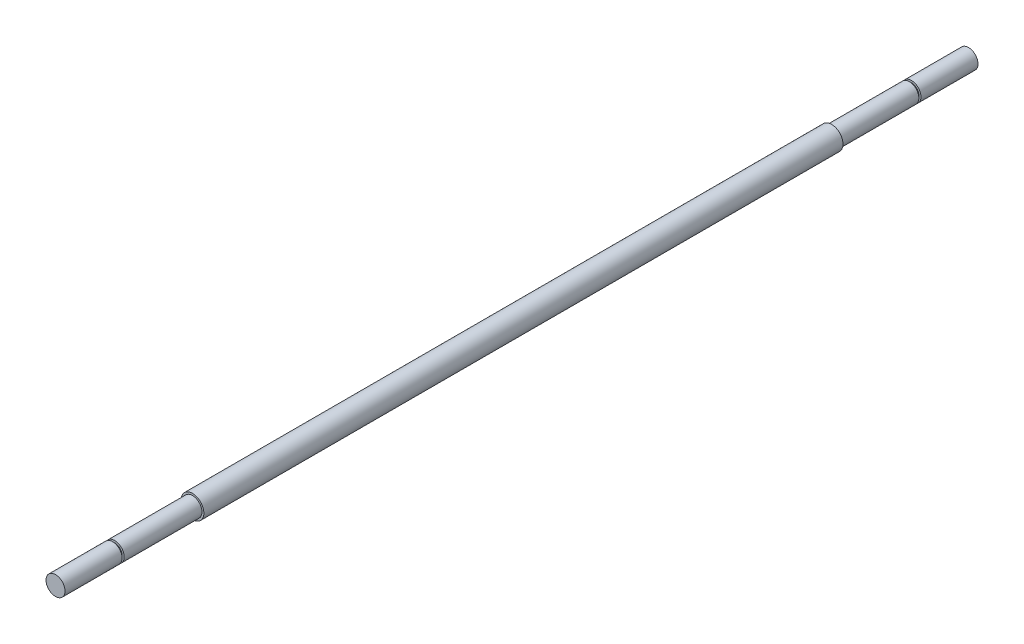
SolidWorks part; units mm, degrees
ref_plane "Front Plane" through (0, 0, 0) normal (0, 0, 1) x (1, 0, 0)
ref_plane "Top Plane" through (0, 0, 0) normal (0, 1, 0) x (1, 0, 0)
ref_plane "Right Plane" through (0, 0, 0) normal (1, 0, 0) x (0, 0, -1)
sketch "Sketch1" plane through (0, 0, 0) normal (0, 0, 1) x (1, 0, 0)
  circle A0 centre (0, 0) radius 7.62
  dimension "D1" = 15.24
extrude "Boss-Extrude1" add sketch "Sketch1" along normal blind 609.6
fillet "Fillet1" radius 0.25 2 edges at (7.62, 0, 0) (7.62, 0, 609.6)
sketch "Sketch2" plane through (0, 0, 0) normal (0, 1, 0) x (1, 0, 0)
  line L0 (7.62, -609.35) -> (7.62, -0.25) construction
  line L1 (6.35, -91.44) -> (7.62, -91.44)
  line L2 (6.35, -91.44) -> (6.35, 0)
  line L3 (6.35, 0) -> (7.62, 0)
  line L4 (7.62, -91.44) -> (7.62, 0)
  line L5 (0, -0.7802) -> (0, -54.9172) construction
  line L7 (7.37, 0) -> (-7.37, 0) construction
  point P0 (7.62, -26.8365)
  dimension "D1" = 6.35
  dimension "D2" = 91.44
revolve "Cut-Revolve2" cut sketch "Sketch2" angle 360 about L5
sketch "Sketch3" plane through (0, 0, 0) normal (0, 1, 0) x (1, 0, 0)
  line L0 (0, 0) -> (0, -609.35) construction
  line L1 (7.62, -609.35) -> (-7.62, -609.35) construction
sketch "Sketch4" plane through (0, 0, 0) normal (0, 1, 0) x (1, 0, 0)
  line L0 (6.35, -91.44) -> (6.35, 0) construction
  line L1 (7.6708, -38.1) -> (5.0292, -38.1)
  line L2 (7.6708, -38.1) -> (7.6708, -39.497)
  line L3 (7.6708, -39.497) -> (5.0292, -39.497)
  line L4 (5.0292, -38.1) -> (5.0292, -39.497)
  line L5 (7.6708, -38.1) -> (5.0292, -39.497) construction
  line L6 (7.6708, -39.497) -> (5.0292, -38.1) construction
  line L7 (6.35, 0) -> (-6.35, 0) construction
  line L8 (0, 0) -> (0, -609.35) construction
  point P0 (6.35, -38.7985)
  dimension "D1" = 38.1
  dimension "D2" = 1.397
  dimension "D3" = 5.0292
revolve "Cut-Revolve3" cut sketch "Sketch4" angle 360 about L0
ref_plane "Plane2" through (0, 0, 304.8) normal (0, 0, 1) x (1, 0, 0)
mirror "Mirror1" about plane through (0, 0, 304.8) normal (0, 0, 1) of "Cut-Revolve2", "Cut-Revolve3"
